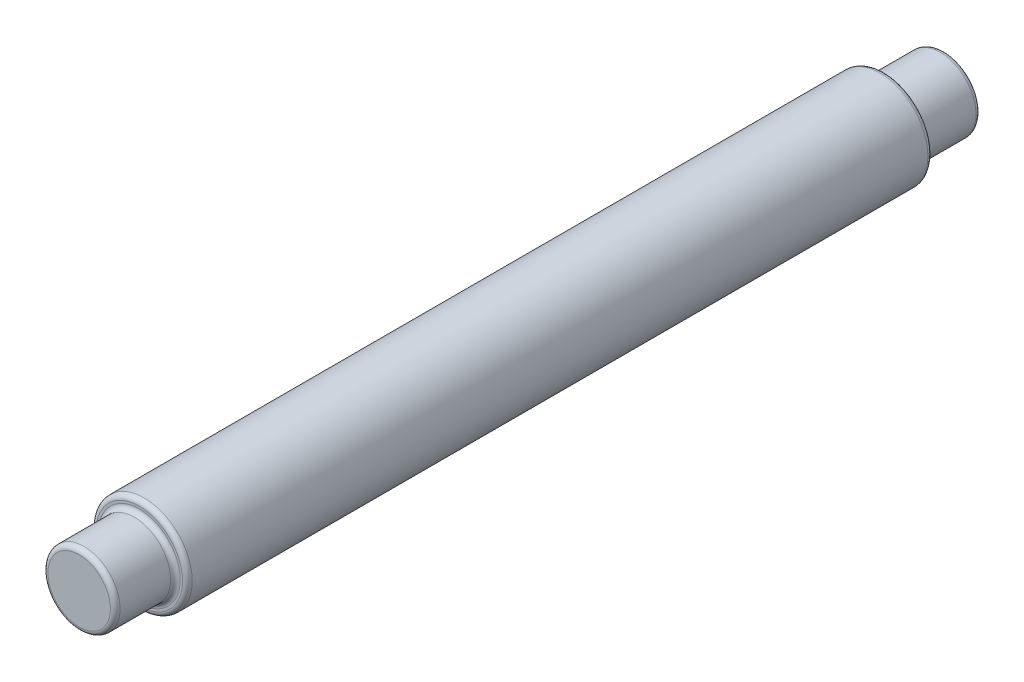
SolidWorks part; units mm, degrees
ref_plane "Front Plane" through (0, 0, 0) normal (0, 0, 1) x (1, 0, 0)
ref_plane "Top Plane" through (0, 0, 0) normal (0, 1, 0) x (1, 0, 0)
ref_plane "Right Plane" through (0, 0, 0) normal (1, 0, 0) x (0, 0, -1)
sketch "Sketch1" plane through (0, 0, 0) normal (0, 0, 1) x (1, 0, 0)
  circle A0 centre (0, 0) radius 1
  dimension "D1" = 2
extrude "Boss-Extrude1" add sketch "Sketch1" along normal mid plane 15.5
sketch "Sketch2" plane through (0, 0, 0) normal (0, 0, 1) x (1, 0, 0)
  circle A0 centre (0, 0) radius 0.75
  dimension "D1" = 1.5
extrude "Boss-Extrude2" add sketch "Sketch2" along normal mid plane 18
fillet "Fillet1" radius 0.1 6 edges at (0.75, 0, -7.75) (1, 0, 7.75) (1, 0, -7.75) (0.75, 0, 7.75) (0.75, 0, 9) (0.75, 0, -9)
